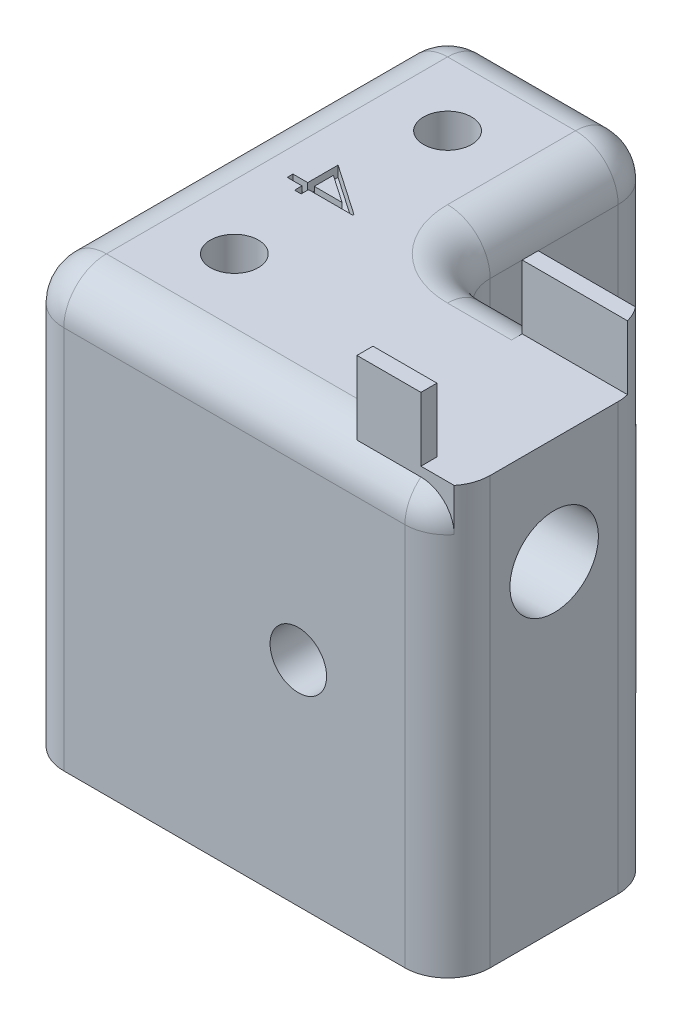
SolidWorks part; units mm, degrees
ref_plane "Alzado" through (0, 0, 0) normal (0, 0, 1) x (1, 0, 0)
ref_plane "Planta" through (0, 0, 0) normal (0, 1, 0) x (1, 0, 0)
ref_plane "Vista lateral" through (0, 0, 0) normal (1, 0, 0) x (0, 0, -1)
sketch "Croquis1" plane through (0, 0, 0) normal (0, 1, 0) x (1, 0, 0)
  line L0 (0, 0) -> (40, 0)
  line L1 (40, 0) -> (40, 20)
  line L2 (40, 20) -> (20, 20)
  line L3 (20, 20) -> (20, 40)
  line L4 (20, 40) -> (0, 40)
  line L5 (0, 40) -> (0, 0)
extrude "Saliente-Extruir1" add sketch "Croquis1" along normal blind 40
fillet "Redondeo3" radius 4 12 edges at (40, 20, 0) (0, 20, 0) (0, 20, -40) (20, 20, -40) (20, 20, -20) (40, 20, -20) (40, 40, -10) (20, 40, 0) (0, 40, -20) (10, 40, -40) (30, 40, -20) (20, 40, -30)
sketch "Croquis4" plane through (0, 40, 0) normal (0, 1, 0) x (1, 0, 0)
  line L0 (10, 30) -> (10, 10) construction
  circle A0 centre (10, 30) radius 2.25
  circle A1 centre (10, 10) radius 2.25
extrude "Cortar-Extruir3" cut sketch "Croquis4" against normal through all
sketch "Croquis5" plane through (40, 0, 0) normal (1, 0, 0) x (0, 0, -1)
  line L0 (4, 0) -> (10, 0) construction
  line L1 (4, 36) -> (4, 0) construction
  line L2 (4, 0) -> (16, 0) construction
  line L3 (10, 0) -> (10, 30) construction
  circle A0 centre (10, 30) radius 4.15
extrude "Cortar-Extruir4" cut sketch "Croquis5" against normal blind 25
sketch "Croquis8" plane through (0, 40, 0) normal (0, 1, 0) x (1, 0, 0)
  line L0 (6.2674, 36) -> (6.2674, 4) construction
  line L1 (16, 36) -> (4, 36) construction
  line L2 (4, 4) -> (36, 4) construction
  text T0 "4" font "Century Gothic" height 6
extrude "Cortar-Extruir6" cut sketch "Croquis8" against normal blind 1
sketch "Croquis9" plane through (0, 0, 0) normal (0, 0, 1) x (1, 0, 0)
  line L0 (4, 0) -> (36, 0) construction
  line L1 (4, 36) -> (4, 0) construction
  circle A0 centre (26, 20) radius 2.65
  dimension "D1" = 20
  dimension "D2" = 22
  dimension "D3" = 5.3
extrude "Cortar-Extruir7" cut sketch "Croquis9" against normal blind 24
sketch "Croquis11" plane through (0, 40, 0) normal (0, 1, 0) x (1, 0, 0)
  line L0 (36, 16) -> (24, 16) construction
  line L1 (30, 18.5) -> (39.1225, 18.5)
  line L2 (30, 18.5) -> (30, 1.5)
  line L3 (30, 1.5) -> (39.1225, 1.5)
  line L4 (40, 16) -> (40, 4)
  line L5 (4, 4) -> (36, 4) construction
  line L6 (40, 16) -> (40, 4) construction
  arc A0 (39.1225, 1.5) -> (40, 4) centre (36, 4) ccw
  arc A1 (40, 16) -> (39.1225, 18.5) centre (36, 16) ccw
  dimension "D1" = 2.5
  dimension "D2" = 2.5
  dimension "D4" = 0
extrude "Saliente-Extruir2" add sketch "Croquis11" against normal blind 5
sketch "Croquis12" plane through (0, 40, 0) normal (0, 1, 0) x (1, 0, 0)
  line L0 (36, 3) -> (36, 1.5)
  line L1 (30, 18.5) -> (39.1225, 18.5)
  line L2 (30, 18.5) -> (30, 17)
  line L3 (30, 17) -> (39.873, 17)
  line L5 (30, 1.5) -> (36, 1.5)
  line L6 (30, 1.5) -> (30, 3)
  line L7 (30, 3) -> (36, 3)
  arc A0 (40, 16) -> (39.1225, 18.5) centre (36, 16) ccw construction
  arc A2 (39.873, 17) -> (39.1225, 18.5) centre (36, 16) ccw
  dimension "D1" = 14
  dimension "D2" = 1.5
  dimension "D3" = 6
extrude "Saliente-Extruir3" add sketch "Croquis12" along normal blind 6
